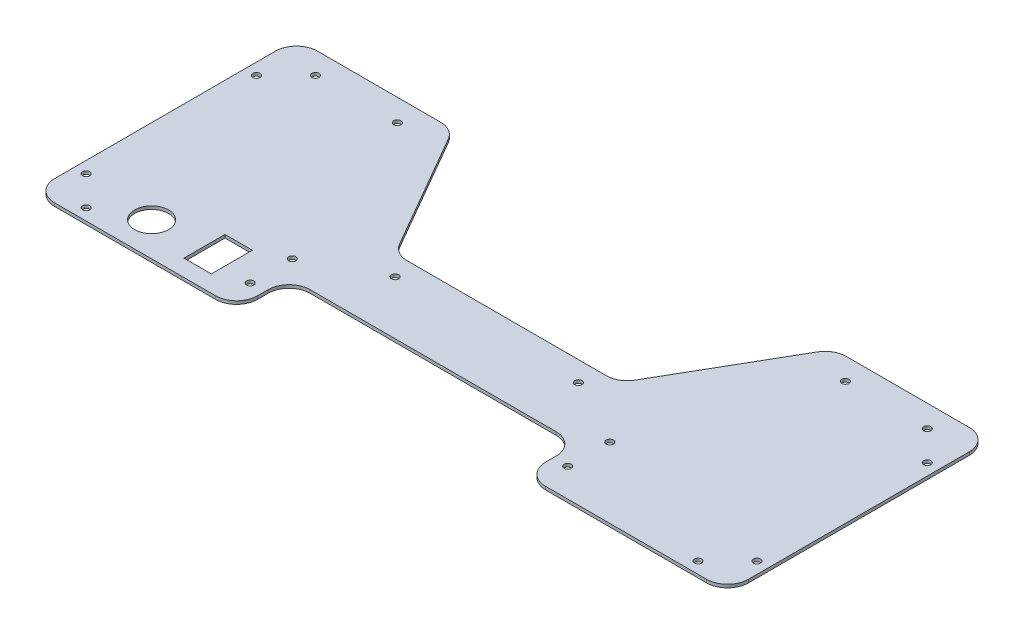
SolidWorks part; units mm, degrees
material "Alliage 1060"
ref_plane "Front" through (0, 0, 0) normal (0, 0, 1) x (1, 0, 0)
ref_plane "Top" through (0, 0, 0) normal (0, 1, 0) x (1, 0, 0)
ref_plane "Right" through (0, 0, 0) normal (1, 0, 0) x (0, 0, -1)
sketch "Esquisse1" plane through (0, 0, 0) normal (0, 1, 0) x (1, 0, 0)
  line L0 (0, 0) -> (0, 120) construction
  line L1 (-165, 120) -> (165, 120) construction
  line L2 (-165, 120) -> (-165, -30) construction
  line L3 (-165, -30) -> (-68.5, -30)
  line L4 (165, 120) -> (165, -30) construction
  line L5 (-165, -30) -> (-165, 90)
  line L6 (-165, 90) -> (-93.5278, 90) construction
  line L7 (-93.5278, 90) -> (-56, 25) construction
  line L8 (-56, 25) -> (56, 25) construction
  line L9 (56, 25) -> (93.5278, 90) construction
  line L10 (93.5278, 90) -> (165, 90) construction
  line L11 (165, 90) -> (165, -30)
  line L12 (-68.5, -30) -> (-68.5, -5)
  line L13 (-68.5, -5) -> (68.5, -5)
  line L14 (68.5, -5) -> (68.5, -30)
  line L15 (68.5, -30) -> (165, -30)
  line L16 (-165, 90) -> (-165, 95)
  line L17 (-165, 95) -> (-90.641, 95)
  line L18 (-90.641, 95) -> (-53.1132, 30)
  line L19 (-53.1132, 30) -> (53.1132, 30)
  line L20 (53.1132, 30) -> (90.641, 95)
  line L21 (90.641, 95) -> (165, 95)
  line L22 (165, 95) -> (165, 90)
  line L23 (-93.5278, 90) -> (-93.5278, 95) construction
  line L24 (-93.5278, 90) -> (-89.1976, 92.5) construction
  line L25 (-53.1132, 30) -> (-53.1132, 25) construction
  point P7 (0, 25)
  point P16 (0, -5)
  dimension "D1" = 120
  dimension "D5" = 30
  dimension "D2" = 120
  dimension "D3" = 330
  dimension "D4" = 150
  dimension "D6" = 65
  dimension "D7" = 56
  dimension "D8" = 25
  dimension "D9" = 137
  dimension "D10" = 5
extrude "Boss.-Extru.1" add sketch "Esquisse1" along normal blind 1.5
fillet "Congé2" radius 10 12 edges at (-165, 0.75, 30) (68.5, 0.75, 30) (68.5, 0.75, 5) (-68.5, 0.75, 5) (-68.5, 0.75, 30) (165, 0.75, 30) (90.641, 0.75, -95) (165, 0.75, -95) (53.1132, 0.75, -30) (-53.1132, 0.75, -30) (-90.641, 0.75, -95) (-165, 0.75, -95)
hole_wizard "Dégagement M31" positions "Esquisse2" profile "Esquisse3" hole size "M3" standard "Ansi Metric" end condition through all
sketch "Esquisse2" plane through (0, 1.5, 0) normal (0, 1, 0) x (1, 0, 0)
  line L1 (-155, -30) -> (-78.5, -30) construction
  line L2 (-165, 85) -> (-165, -20) construction
  line L3 (-75.5, -16.5) -> (-75.5, 3.5) construction
  line L4 (0, -50) -> (0, 50) construction
  line L5 (-145.5, -30) -> (-145.5, -24.5) construction
  line L6 (-145.5, -24.5) -> (-159.5, -10.5) construction
  line L7 (-159.5, -10.5) -> (-165, -10.5) construction
  line L9 (-165, 70.5) -> (-159.5, 70.5) construction
  line L10 (-159.5, 70.5) -> (-145.5, 84.5) construction
  line L11 (-145.5, 84.5) -> (-145.5, 90) construction
  line L17 (-106.53, 84.5) -> (-145.5, 84.5) construction
  point P0 (-75.5, -16.5)
  point P12 (-75.5, 3.5)
  point P22 (75.5, -16.5)
  point P23 (75.5, 3.5)
  point P26 (-145.5, -24.5)
  point P28 (-159.5, -10.5)
  point P34 (-159.5, 70.5)
  point P36 (-145.5, 84.5)
  point P52 (145.5, -24.5)
  point P53 (159.5, -10.5)
  point P54 (145.5, 84.5)
  point P55 (159.5, 70.5)
  point P56 (-43.58, 20.5)
  point P77 (43.58, 20.5)
  point P85 (-106.53, 84.5)
  point P101 (106.53, 84.5)
  dimension "D1" = 13.5
  dimension "D2" = 89.5
  dimension "D3" = 20
  dimension "D4" = 135
  dimension "D5" = 5.5
  dimension "D6" = 19.5
  dimension "D7" = 120
  dimension "D8" = 50.5
  dimension "D9" = 121.42
  dimension "D14" = 58.47
sketch "Esquisse3" plane through (-75.5, 1.5, 16.5) normal (1, 0, 0) x (0, 0, 1)
  line L0 (0, 0) -> (0, 1.5)
  line L1 (0, 1.5) -> (1.7, 1.5)
  line L2 (1.7, 1.5) -> (1.7, 0)
  line L5 (1.7, 0) -> (0, 0)
  line L11 (0, -6.35) -> (0, 107.95) construction
  dimension "Diamètre du perçage jusqu'au prochain" = 3.4
  dimension "Profondeur du perçage jusqu'au prochain" = 1.5
sketch "Esquisse4" plane through (0, 1.5, 0) normal (0, 1, 0) x (1, 0, 0)
  line L0 (-101.5, -2.5) -> (-88.5, -22) construction
  line L1 (-101.5, -2.5) -> (-88.5, -2.5)
  line L2 (-101.5, -2.5) -> (-101.5, -22)
  line L3 (-101.5, -22) -> (-88.5, -22)
  line L4 (-88.5, -2.5) -> (-88.5, -22)
  line L5 (-155, -30) -> (-78.5, -30) construction
  line L7 (-68.5, -20) -> (-68.5, -15) construction
  circle A0 centre (-125, -13.9) radius 8.1
  point P6 (-91.6798, -14)
  point P9 (0, 0)
  point P10 (-121.7265, -14)
  point P11 (-120.7678, -15.2797)
  point P12 (-95, -12.25)
  dimension "D3" = 16.2
  dimension "D1" = 13
  dimension "D2" = 19.5
  dimension "D4" = 30
  dimension "D5" = 8
  dimension "D6" = 20
extrude "Enlèv. mat.-Extru.1" cut sketch "Esquisse4" against normal through all
